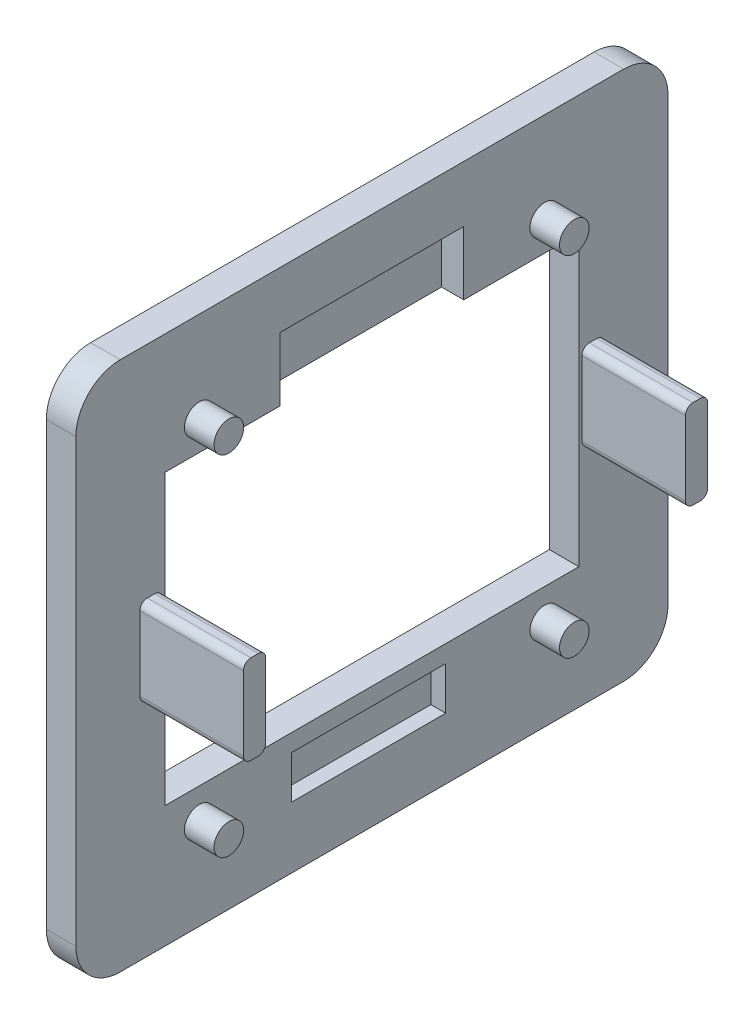
SolidWorks part; units mm, degrees
ref_plane "Plan de face" through (0, 0, 0) normal (0, 0, 1) x (1, 0, 0)
ref_plane "Plan de dessus" through (0, 0, 0) normal (0, 1, 0) x (1, 0, 0)
ref_plane "Plan de droite" through (0, 0, 0) normal (1, 0, 0) x (0, 0, -1)
sketch "Esquisse3" plane through (-2.8201, 0, 0) normal (-1, 0, 0) x (0, 0, 1)
  line L6 (0, 0) -> (0, 27.543) construction
  line L7 (-13.78, -13.91) -> (13.78, -13.91) construction
  line L8 (-20, 17.91) -> (20, 17.91)
  line L9 (-20, 17.91) -> (-20, -17.91)
  line L10 (-20, -17.91) -> (20, -17.91)
  line L11 (20, 17.91) -> (20, -17.91)
  line L12 (-13.98, 9.81) -> (-13.98, -9.69)
  line L13 (-13.98, -9.69) -> (13.98, -9.69)
  line L14 (13.98, -9.69) -> (13.98, 9.81)
  line L15 (13.98, 9.81) -> (6, 9.81)
  line L16 (6, 9.81) -> (-6, 9.81)
  line L17 (-6, 9.81) -> (-13.98, 9.81)
  line L18 (-13.98, 9.81) -> (-13.98, -9.69)
  line L19 (-13.98, -9.69) -> (13.98, -9.69)
  line L20 (13.98, -9.69) -> (13.98, 9.81)
  line L21 (13.98, 9.81) -> (6, 9.81)
  line L22 (6, 9.81) -> (-6, 9.81)
  line L23 (-6, 9.81) -> (-13.98, 9.81)
  line L24 (-6, 13.91) -> (-13.78, 13.91) construction
  dimension "D2" = 40
  dimension "D3" = 4
  dimension "D4" = 4
  dimension "D1" = 0.2
extrude "Boss.-Extru.1" add sketch "Esquisse3" along normal blind 2
sketch "Esquisse4" plane through (-2.8201, 0, 0) normal (1, 0, 0) x (0, 0, -1)
  circle A0 centre (-11.6687, 11.7787) radius 1 construction
  circle A1 centre (-11.6687, -11.7787) radius 1 construction
  circle A2 centre (11.6687, -11.7787) radius 1 construction
  circle A3 centre (11.6687, 11.7787) radius 1 construction
  circle A4 centre (-11.6687, 11.7787) radius 1
  circle A5 centre (-11.6687, -11.7787) radius 1
  circle A6 centre (11.6687, -11.7787) radius 1
  circle A7 centre (11.6687, 11.7787) radius 1
extrude "Boss.-Extru.2" add sketch "Esquisse4" along normal blind 2
sketch "Esquisse5" plane through (-2.8201, 0, 0) normal (1, 0, 0) x (0, 0, -1)
  line L8 (4.98, -13.76) -> (4.98, -10.86)
  line L9 (4.98, -10.86) -> (-5.42, -10.86)
  line L10 (-5.42, -13.76) -> (4.98, -13.76)
  line L11 (-5.42, -10.86) -> (-5.42, -13.76)
  line L12 (4.98, -13.76) -> (4.98, -10.86)
  line L13 (4.98, -10.86) -> (-5.42, -10.86)
  line L14 (-5.42, -13.76) -> (4.98, -13.76)
  line L15 (-5.42, -10.86) -> (-5.42, -13.76)
  dimension "D1" = 0.2
extrude "Enlèv. mat.-Extru.1" cut sketch "Esquisse5" against normal blind 1
sketch "Esquisse6" plane through (-2.8201, 0, 0) normal (1, 0, 0) x (0, 0, -1)
  line L7 (-6.2, 9.61) -> (6.2, 9.61)
  line L10 (-6.2, 14.11) -> (6.2, 14.11)
  line L11 (6.2, 14.11) -> (6.2, 9.61)
  line L12 (-6.2, 9.61) -> (-6.2, 14.11)
  line L13 (-6.2, 14.11) -> (6.2, 14.11)
  line L14 (6.2, 14.11) -> (6.2, 9.61)
  line L15 (-6.2, 9.61) -> (-6.2, 14.11)
  dimension "D1" = 0.2
extrude "Enlèv. mat.-Extru.2" cut sketch "Esquisse6" against normal blind 1.5
sketch "Esquisse8" plane through (-2.8201, 0, 0) normal (1, 0, 0) x (0, 0, -1)
  line L0 (-13.98, -9.69) -> (-13.98, 9.81) construction
  line L1 (-15.68, 3.06) -> (-14.18, 3.06)
  line L2 (-15.68, 3.06) -> (-15.68, -2.94)
  line L3 (-15.68, -2.94) -> (-14.18, -2.94)
  line L4 (-14.18, 3.06) -> (-14.18, -2.94)
  line L5 (-13.98, 0.06) -> (-16.6137, 0.06) construction
  dimension "D1" = 0.2
  dimension "D2" = 1.5
  dimension "D3" = 6
extrude "Boss.-Extru.3" add sketch "Esquisse8" along normal blind 7
fillet "Congé1" radius 0.5 4 edges at (0.6799, 3.06, 14.18) (0.6799, 3.06, 15.68) (0.6799, -2.94, 14.18) (0.6799, -2.94, 15.68)
mirror "Symétrie1" about plane through (0, 0, 0) normal (0, 0, 1) of "Congé1", "Boss.-Extru.3"
fillet "Congé2" radius 3 4 edges at (-3.8201, 17.91, -20) (-3.8201, 17.91, 20) (-3.8201, -17.91, 20) (-3.8201, -17.91, -20)
